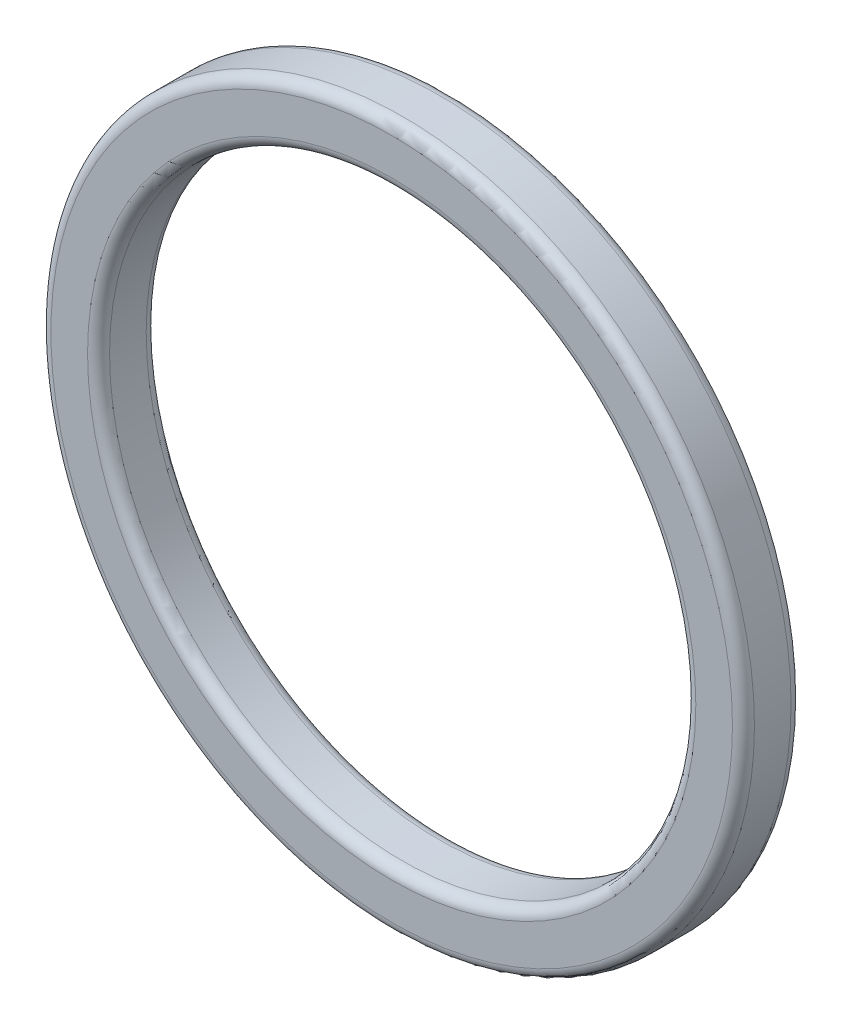
SolidWorks part; units mm, degrees
ref_plane "前视基准面" through (0, 0, 0) normal (0, 0, 1) x (1, 0, 0)
ref_plane "上视基准面" through (0, 0, 0) normal (0, 1, 0) x (1, 0, 0)
ref_plane "右视基准面" through (0, 0, 0) normal (1, 0, 0) x (0, 0, -1)
other "Configuration Table"
sketch "草图1" plane through (0, 0, 0) normal (0, 0, 1) x (1, 0, 0)
  circle A0 centre (0, 0) radius 48
  dimension "diameter" = 96
extrude "Sleeve" add sketch "草图1" along normal blind 8
sketch "草图2" plane through (0, 0, 8) normal (0, 0, 1) x (1, 0, 0)
  circle A0 centre (0, 0) radius 40
  dimension "diameter" = 80
extrude "Bore" cut sketch "草图2" against normal through all
fillet "Rounded_edges" radius 1.5 4 edges at (40, 0, 8) (40, 0, 0) (48, 0, 0) (48, 0, 8)
